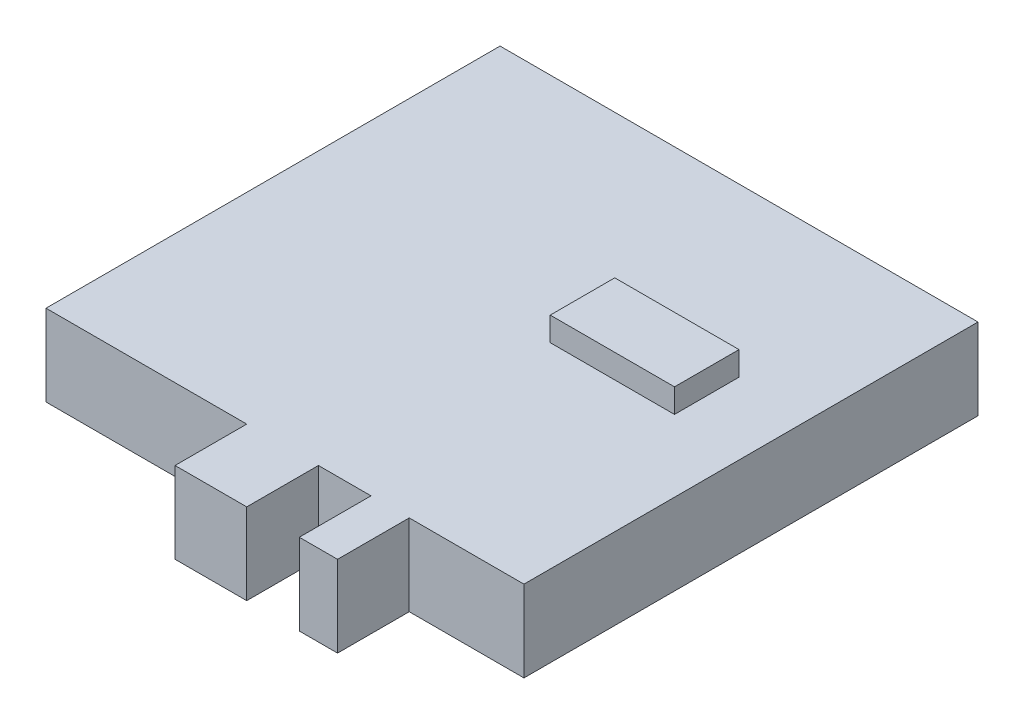
SolidWorks part; units mm, degrees
ref_plane "Front Plane" through (0, 0, 0) normal (0, 0, 1) x (1, 0, 0)
ref_plane "Top Plane" through (0, 0, 0) normal (0, 1, 0) x (1, 0, 0)
ref_plane "Right Plane" through (0, 0, 0) normal (1, 0, 0) x (0, 0, -1)
sketch "Sketch1" plane through (0, 0, 0) normal (0, 1, 0) x (1, 0, 0)
  line L0 (24.9315, -43.415) -> (35.9315, -43.415)
  line L1 (-32.0685, 51.585) -> (67.9315, 51.585)
  line L2 (-32.0685, 51.585) -> (-32.0685, -43.415)
  line L3 (-32.0685, -43.415) -> (9.9315, -43.415)
  line L4 (67.9315, 51.585) -> (67.9315, -43.415)
  line L5 (26.9315, 16.585) -> (52.9315, 16.585)
  line L6 (26.9315, 16.585) -> (26.9315, 3.085)
  line L7 (26.9315, 3.085) -> (52.9315, 3.085)
  line L8 (52.9315, 16.585) -> (52.9315, 3.085)
  line L10 (9.9315, -43.415) -> (9.9315, -58.415)
  line L11 (9.9315, -58.415) -> (24.9315, -58.415)
  line L12 (24.9315, -43.415) -> (24.9315, -58.415)
  line L14 (43.9315, -43.415) -> (43.9315, -58.415)
  line L15 (43.9315, -58.415) -> (35.9315, -58.415)
  line L16 (35.9315, -43.415) -> (35.9315, -58.415)
  line L17 (43.9315, -43.415) -> (67.9315, -43.415)
  point P16 (0, 0)
  point P17 (0, 0)
  point P18 (67.9315, 51.585)
  point P19 (0, 0)
  dimension "D1" = 100
  dimension "D2" = 95
  dimension "D3" = 26
  dimension "D4" = 13.5
  dimension "D5" = 15
  dimension "D6" = 35
  dimension "D7" = 42
  dimension "D8" = 24
  dimension "D9" = 15
  dimension "D10" = 8
  dimension "D11" = 15
extrude "Boss-Extrude9" add sketch "Sketch1" along normal blind 17 contours L14 L17 L4 L1 L2 L3 L10 L11 L12 L0 L16 L15 L5 L8 L7 L6
sketch "Sketch5" plane through (0, 17, 0) normal (0, 1, 0) x (1, 0, 0)
  line L0 (67.9315, 51.585) -> (67.9315, -43.415) construction
  line L1 (26.9315, 16.585) -> (52.9315, 16.585)
  line L2 (26.9315, 16.585) -> (26.9315, 3.085)
  line L3 (26.9315, 3.085) -> (52.9315, 3.085)
  line L4 (52.9315, 16.585) -> (52.9315, 3.085)
  line L5 (-32.0685, 51.585) -> (67.9315, 51.585) construction
  dimension "D1" = 26
  dimension "D2" = 13.5
  dimension "D3" = 15
  dimension "D4" = 35
extrude "Boss-Extrude10" add sketch "Sketch5" along normal blind 5
